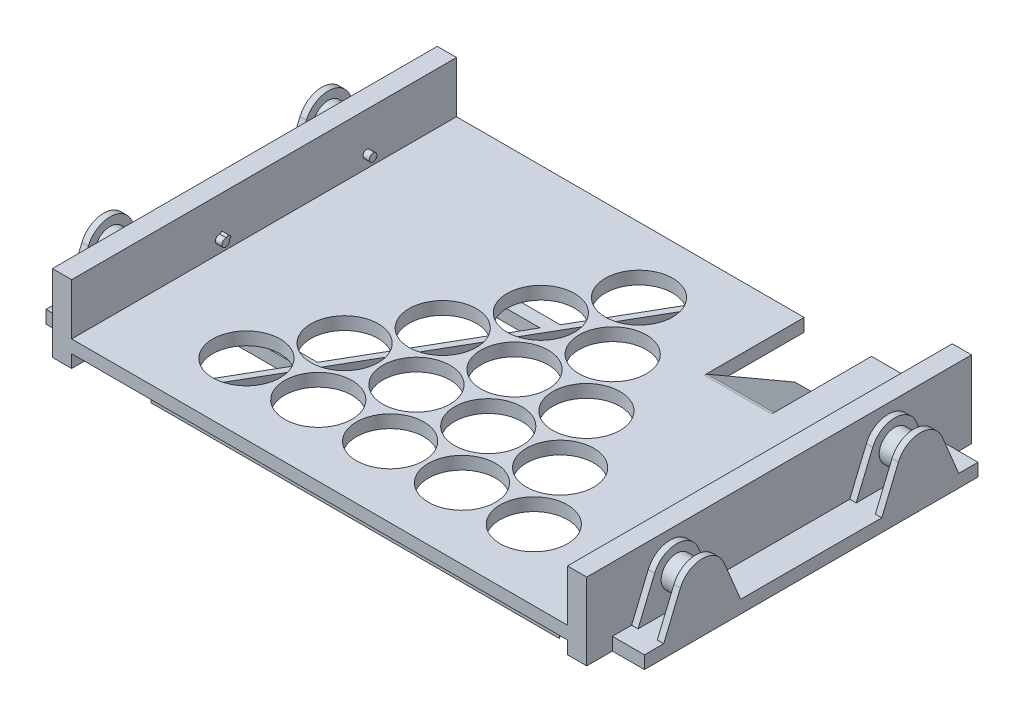
SolidWorks part; units mm, degrees
ref_plane "前视基准面" through (0, 0, 0) normal (0, 0, 1) x (1, 0, 0)
ref_plane "上视基准面" through (0, 0, 0) normal (0, 1, 0) x (1, 0, 0)
ref_plane "右视基准面" through (0, 0, 0) normal (1, 0, 0) x (0, 0, -1)
sketch "草图2" plane through (0, 0, 0) normal (0, 1, 0) x (1, 0, 0)
  line L1 (-16.5, -20) -> (400, -20)
  line L2 (-16.5, -20) -> (-16.5, 280)
  line L3 (-16.5, 280) -> (400, 280)
  line L4 (400, -20) -> (400, 280)
extrude "凸台-拉伸1" add sketch "草图2" along normal blind 60
sketch "草图3" plane through (0, 60, 0) normal (0, 1, 0) x (1, 0, 0)
  line L1 (400, 35) -> (330, 35) construction
  line L2 (400, 35) -> (400, -20) construction
  line L5 (303.75, 35) -> (235.0761, 153.9468) construction
  circle A0 centre (303.75, 35) radius 26.25
  circle A1 centre (247.75, 35) radius 26.25
  circle A2 centre (191.75, 35) radius 26.25
  circle A3 centre (135.75, 35) radius 26.25
  circle A4 centre (79.75, 35) radius 26.25
  circle A5 centre (219.75, 83.4974) radius 26.25
  circle A6 centre (275.75, 83.4974) radius 26.25
  circle A7 centre (163.75, 83.4974) radius 26.25
  circle A8 centre (107.75, 83.4974) radius 26.25
  circle A9 centre (191.75, 131.9948) radius 26.25
  circle A10 centre (247.75, 131.9948) radius 26.25
  circle A11 centre (135.75, 131.9948) radius 26.25
  circle A12 centre (163.75, 180.4923) radius 26.25
  circle A13 centre (219.75, 180.4923) radius 26.25
  circle A14 centre (191.75, 228.9897) radius 26.25
  circle A15 centre (295.75, 203.4974) radius 26.25
  dimension "D1" = 5
extrude "切除-拉伸1" [suppressed] cut sketch "草图3" against normal blind 30
sketch "草图6" plane through (400, 0, 0) normal (1, 0, 0) x (0, 0, -1)
  line L0 (0, 10) -> (15, 10)
  line L2 (15, 10) -> (27.9585, 41.1006)
  line L3 (260, 10) -> (260, 0)
  line L4 (75, 10) -> (62.0415, 41.1006)
  line L5 (90, 10) -> (75, 10)
  line L8 (170, 10) -> (185, 10)
  line L9 (185, 10) -> (197.9585, 41.1006)
  line L10 (245, 10) -> (232.0415, 41.1006)
  line L11 (0, 10) -> (0, 0)
  line L12 (0, 0) -> (260, 0)
  line L14 (260, 10) -> (245, 10)
  line L15 (90, 10) -> (170, 10)
  line L16 (0, 0) -> (260, 0)
  arc A0 (62.0415, 41.1006) -> (27.9585, 41.1006) centre (45, 34) ccw
  arc A1 (197.9585, 41.1006) -> (232.0415, 41.1006) centre (215, 34) cw
extrude "凸台-拉伸4" add sketch "草图6" along normal blind 5
sketch "草图5" plane through (400, 0, 0) normal (1, 0, 0) x (0, 0, -1)
  circle A0 centre (215, 34) radius 12
  circle A1 centre (45, 34) radius 12
extrude "凸台-拉伸3" add sketch "草图5" along normal blind 20
sketch "草图8" plane through (405, 0, 0) normal (1, 0, 0) x (0, 0, -1)
  line L1 (0, 0) -> (260, 0)
  line L2 (0, 0) -> (0, 10)
  line L3 (0, 10) -> (260, 10)
  line L4 (260, 0) -> (260, 10)
extrude "凸台-拉伸5" add sketch "草图8" along normal blind 15
sketch "草图9" plane through (420, 0, 0) normal (1, 0, 0) x (0, 0, -1)
  line L0 (15, 10) -> (27.9585, 41.1006)
  line L1 (0, 0) -> (260, 0)
  line L2 (0, 0) -> (0, 10)
  line L3 (0, 10) -> (15, 10)
  line L4 (260, 0) -> (260, 10)
  line L5 (62.0415, 41.1006) -> (75, 10)
  line L6 (185, 10) -> (197.9585, 41.1006)
  line L7 (232.0415, 41.1006) -> (245, 10)
  line L8 (245, 10) -> (260, 10)
  line L9 (75, 10) -> (185, 10)
  arc A0 (62.0415, 41.1006) -> (27.9585, 41.1006) centre (45, 34) ccw
  arc A1 (232.0415, 41.1006) -> (197.9585, 41.1006) centre (215, 34) ccw
extrude "凸台-拉伸6" add sketch "草图9" along normal blind 5
sketch "草图11" plane through (-16.5, 0, 0) normal (-1, 0, 0) x (0, 0, 1)
  line L0 (-260, 10) -> (-245, 10)
  line L1 (-245, 10) -> (-232.0415, 41.1006)
  line L2 (-260, 10) -> (-260, 0)
  line L3 (-185, 10) -> (-197.9585, 41.1006)
  line L4 (-170, 10) -> (-185, 10)
  line L5 (0, 10) -> (0, 0)
  line L6 (-90, 10) -> (-75, 10)
  line L7 (-75, 10) -> (-62.0415, 41.1006)
  line L8 (-15, 10) -> (-27.9585, 41.1006)
  line L10 (-260, 0) -> (0, 0)
  line L12 (0, 10) -> (-15, 10)
  line L13 (-170, 10) -> (-90, 10)
  arc A0 (-197.9585, 41.1006) -> (-232.0415, 41.1006) centre (-215, 34) ccw
  arc A1 (-62.0415, 41.1006) -> (-27.9585, 41.1006) centre (-45, 34) cw
extrude "凸台-拉伸8" add sketch "草图11" along normal blind 5
sketch "草图10" plane through (-16.5, 0, 0) normal (-1, 0, 0) x (0, 0, 1)
  circle A0 centre (-45, 34) radius 12
  circle A1 centre (-215, 34) radius 12
extrude "凸台-拉伸7" add sketch "草图10" along normal blind 20
sketch "草图13" plane through (-21.5, 0, 0) normal (-1, 0, 0) x (0, 0, 1)
  line L1 (-260, 10) -> (0, 10)
  line L2 (-260, 10) -> (-260, 0)
  line L3 (-260, 0) -> (0, 0)
  line L4 (0, 10) -> (0, 0)
extrude "凸台-拉伸10" add sketch "草图13" along normal blind 15
sketch "草图14" plane through (-36.5, 0, 0) normal (-1, 0, 0) x (0, 0, 1)
  line L0 (-260, 10) -> (-245, 10)
  line L1 (-245, 10) -> (-232.0415, 41.1006)
  line L2 (-215, 34) -> (-215, 9.9999) construction
  line L3 (-185, 10) -> (-197.9585, 41.1006)
  line L4 (-170, 10) -> (-185, 10)
  line L5 (-130, 0) -> (-130, 60) construction
  line L6 (-90, 10) -> (-75, 10)
  line L7 (-75, 10) -> (-62.0415, 41.1006)
  line L8 (-15, 10) -> (-27.9585, 41.1006)
  line L9 (-260, 10) -> (-260, 0)
  line L10 (-260, 0) -> (0, 0)
  line L11 (0, 0) -> (0, 10)
  line L12 (0, 10) -> (-15, 10)
  line L13 (-170, 10) -> (-90, 10)
  line L14 (-260, 0) -> (0, 0)
  arc A0 (-197.9585, 41.1006) -> (-232.0415, 41.1006) centre (-215, 34) ccw
  arc A1 (-62.0415, 41.1006) -> (-27.9585, 41.1006) centre (-45, 34) cw
  line M1 (-260, 10) -> (-260, 0)
  line M2 (-260, 0) -> (0, 0)
  line M3 (0, 0) -> (0, 10)
  line M4 (0, 10) -> (-260, 10)
extrude "凸台-拉伸11" add sketch "草图14" along normal blind 5 contours M4 M1 M2 M3 | L3 A0 L1 M4 | A1 L7 L8 M4
sketch "草图15" plane through (0, 60, 0) normal (0, 1, 0) x (1, 0, 0)
  line L1 (400, 280) -> (-16.5, 280) construction
  line L3 (-16.5, -20) -> (400, -20) construction
  line L4 (-1.5, 280) -> (385, 280)
  line L5 (-1.5, 280) -> (-1.5, -20)
  line L6 (-1.5, -20) -> (385, -20)
  line L7 (385, 280) -> (385, -20)
extrude "切除-拉伸2" cut sketch "草图15" against normal blind 40
sketch "草图16" plane through (0, 20, 0) normal (0, 1, 0) x (1, 0, 0)
  line L0 (400, 35) -> (330, 35) construction
  line L1 (400, 35) -> (400, 0) construction
  line L2 (303.75, 35) -> (235.0761, 153.9468) construction
  circle A0 centre (303.75, 35) radius 26.25
  circle A1 centre (247.75, 35) radius 26.25
  circle A2 centre (191.75, 35) radius 26.25
  circle A3 centre (135.75, 35) radius 26.25
  circle A4 centre (79.75, 35) radius 26.25
  circle A5 centre (219.75, 83.4974) radius 26.25
  circle A6 centre (275.75, 83.4974) radius 26.25
  circle A7 centre (163.75, 83.4974) radius 26.25
  circle A8 centre (107.75, 83.4974) radius 26.25
  circle A9 centre (191.75, 131.9948) radius 26.25
  circle A10 centre (247.75, 131.9948) radius 26.25
  circle A11 centre (135.75, 131.9948) radius 26.25
  circle A12 centre (163.75, 180.4923) radius 26.25
  circle A13 centre (219.75, 180.4923) radius 26.25
  circle A14 centre (191.75, 228.9897) radius 26.25
  circle A15 centre (295.75, 203.4974) radius 26.25 construction
extrude "切除-拉伸3" cut sketch "草图16" against normal blind 10
sketch "草图17" plane through (0, 0, 0) normal (0, -1, 0) x (1, 0, 0)
  line L1 (385, 20) -> (-1.5, 20)
  line L2 (385, 20) -> (385, -280)
  line L3 (385, -280) -> (-1.5, -280)
  line L4 (-1.5, 20) -> (-1.5, -280)
extrude "切除-拉伸4" cut sketch "草图17" against normal blind 10
sketch "草图18" plane through (0, 10, 0) normal (0, -1, 0) x (1, 0, 0)
  line L0 (191.75, -39.0415) -> (403.5279, -39.0415) construction
  line L1 (191.75, -131.9948) -> (191.75, 26.3791) construction
  line L5 (86.75, -12.7915) -> (342.2163, -12.7915)
  line L6 (191.75, -99.6632) -> (191.75, -131.9948) construction
  line L7 (342.2163, -12.7915) -> (309.4604, -69.5264)
  line L8 (309.4604, -69.5264) -> (191.75, -273.4068)
  line L9 (41.2837, -12.7915) -> (74.0396, -69.5264)
  line L10 (74.0396, -69.5264) -> (191.75, -273.4068)
  line L11 (86.75, -12.7915) -> (41.2837, -12.7915)
  line L12 (385, -200) -> (239.9049, -200)
  line L13 (41.2837, -7.7915) -> (350.8766, -7.7915)
  line L14 (-1.5, 20) -> (-1.5, -280) construction
  line L15 (346.5465, -15.2915) -> (350.8766, -7.7915)
  line L16 (346.5465, -15.2915) -> (309.187, -80)
  line L17 (-1.5, -80) -> (74.313, -80)
  line L18 (187.4199, -275.9068) -> (191.75, -283.4068)
  line L19 (187.4199, -275.9068) -> (149.3686, -210)
  line L20 (41.2837, -7.7915) -> (32.6234, -7.7915)
  line L22 (-1.5, -90) -> (80.0865, -90)
  line L24 (-1.5, -210) -> (149.3686, -210)
  line L26 (-1.5, -200) -> (143.5951, -200)
  line L27 (385, -210) -> (234.1314, -210)
  line L28 (385, -90) -> (303.4135, -90)
  line L30 (385, -80) -> (309.187, -80)
  line L31 (74.313, -80) -> (32.6234, -7.7915)
  line L32 (143.5951, -200) -> (80.0865, -90)
  line L33 (234.1314, -210) -> (191.75, -283.4068)
  line L34 (303.4135, -90) -> (239.9049, -200)
  line L35 (-1.5, -80) -> (-21.5, -80)
  line L36 (-21.5, -80) -> (-21.5, -90)
  line L37 (-21.5, -90) -> (-1.5, -90)
  line L38 (-1.5, -200) -> (-21.5, -200)
  line L39 (-21.5, -200) -> (-21.5, -210)
  line L40 (-21.5, -210) -> (-1.5, -210)
  line L41 (385, -80) -> (405, -80)
  line L42 (405, -80) -> (405, -90)
  line L43 (405, -90) -> (385, -90)
  line L44 (385, -200) -> (405, -200)
  line L45 (405, -200) -> (405, -210)
  line L46 (405, -210) -> (385, -210)
  circle A0 centre (191.75, -39.0415) radius 26.25 construction
  circle A1 centre (244.25, -39.0415) radius 26.25 construction
  circle A2 centre (296.75, -39.0415) radius 26.25 construction
  circle A3 centre (86.75, -39.0415) radius 26.25 construction
  circle A4 centre (139.25, -39.0415) radius 26.25 construction
  circle A7 centre (191.75, -129.9741) radius 26.25 construction
  circle A8 centre (165.5, -84.5078) radius 26.25 construction
  circle A9 centre (218, -84.5078) radius 26.25 construction
extrude "凸台-拉伸12" add sketch "草图18" along normal blind 30
sketch "草图19" plane through (0, 10, 0) normal (0, -1, 0) x (1, 0, 0)
  line L5 (-1.5, 20) -> (385, 20)
  line L6 (-1.5, 20) -> (-1.5, -326.9601)
  line L7 (-1.5, -326.9601) -> (385, -326.9601)
  line L8 (385, 20) -> (385, -326.9601)
extrude "切除-拉伸5" cut sketch "草图19" along normal blind 20
sketch "草图20" plane through (-1.5, 0, 0) normal (1, 0, 0) x (0, 0, -1)
  line L0 (95, 30) -> (210, 30) construction
  line L3 (210, 30) -> (280, 30) construction
  line L5 (280, 30) -> (280, 20) construction
  circle A1 centre (95, 30) radius 3
  circle A2 centre (210, 30) radius 3
extrude "凸台-拉伸13" add sketch "草图20" along normal blind 5
sketch "草图22" plane through (385, 0, 0) normal (-1, 0, 0) x (0, 0, 1)
  line L0 (-165, 40) -> (-50, 40) construction
  line L1 (-50, 40) -> (0, 40) construction
  line L2 (0, 40) -> (0, 20) construction
  circle A2 centre (-95, 30) radius 3
  circle A3 centre (-210, 30) radius 3
extrude "凸台-拉伸14" add sketch "草图22" along normal blind 5
sketch "草图23" plane through (3.5, 0, 0) normal (1, 0, 0) x (0, 0, -1)
  line L0 (95, 30) -> (96.1314, 28.8686)
  line L1 (96.1314, 28.8686) -> (99.3134, 32.0506)
  line L2 (99.3134, 32.0506) -> (97.0506, 34.3134)
  line L3 (97.0506, 34.3134) -> (93.8686, 31.1314)
  line L4 (95, 30) -> (93.8686, 31.1314)
extrude "凸台-拉伸15" add sketch "草图23" against normal blind 5
sketch "草图24" plane through (0, 20, 0) normal (0, 1, 0) x (1, 0, 0)
  line L0 (385, 280) -> (295.75, 280) construction
  line L1 (385, 280) -> (-1.5, 280) construction
  line L2 (295.75, 280) -> (295.75, 224.3397) construction
  line L3 (269.5, 280) -> (322, 280)
  line L5 (322, 203.5) -> (322, 280)
  line L6 (269.5, 203.5) -> (269.5, 280)
  line L7 (322, 203.5) -> (269.5, 203.5)
extrude "切除-拉伸6" cut sketch "草图24" against normal blind 10
sketch "草图25" plane through (322, 0, 0) normal (-1, 0, 0) x (0, 0, 1)
  line L0 (-203.5, 20) -> (-272.782, -20)
  line L3 (-203.5, 20) -> (-203.5, 10)
  line L5 (-283.4068, -20) -> (-210, -20) construction
  line L6 (-203.5, 10) -> (-255.4615, -20)
  line L7 (-272.782, -20) -> (-255.4615, -20)
extrude "凸台-拉伸16" add sketch "草图25" along normal blind 52.5
fillet "圆角1" radius 5 1 edges at (295.75, 20, -203.5)
